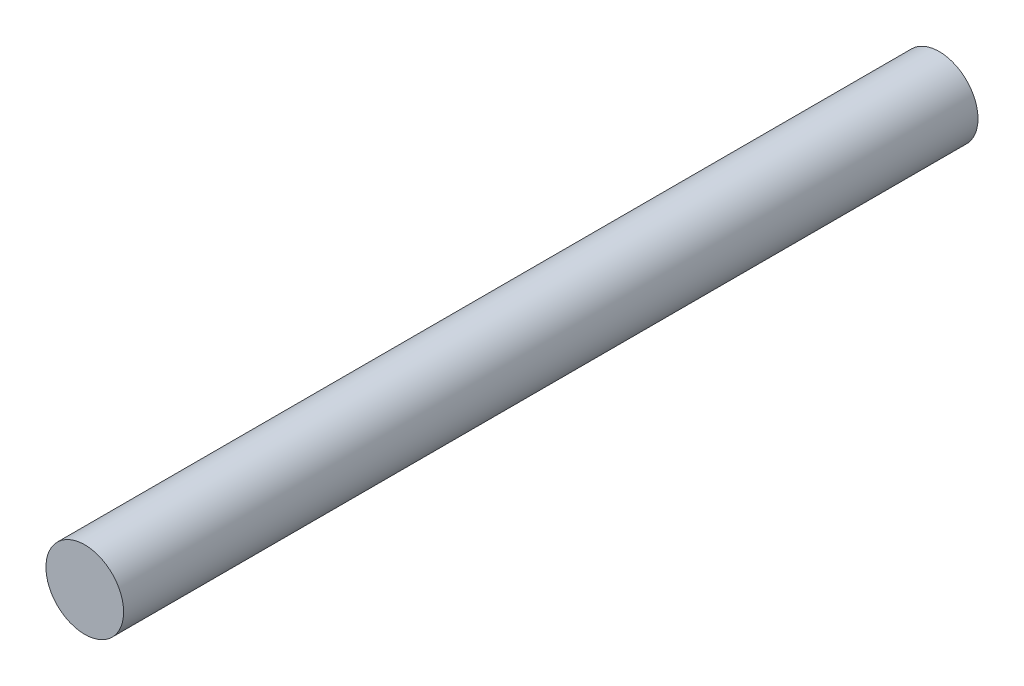
SolidWorks part; units mm, degrees
ref_plane "Front Plane" through (0, 0, 0) normal (0, 0, 1) x (1, 0, 0)
ref_plane "Top Plane" through (0, 0, 0) normal (0, 1, 0) x (1, 0, 0)
ref_plane "Right Plane" through (0, 0, 0) normal (1, 0, 0) x (0, 0, -1)
sketch "Sketch1" plane through (0, 0, 0) normal (0, 0, 1) x (1, 0, 0)
  circle A0 centre (0, 0) radius 1.25
  dimension "D1" = 2.5
extrude "Boss-Extrude1" add sketch "Sketch1" along normal blind 27.5
